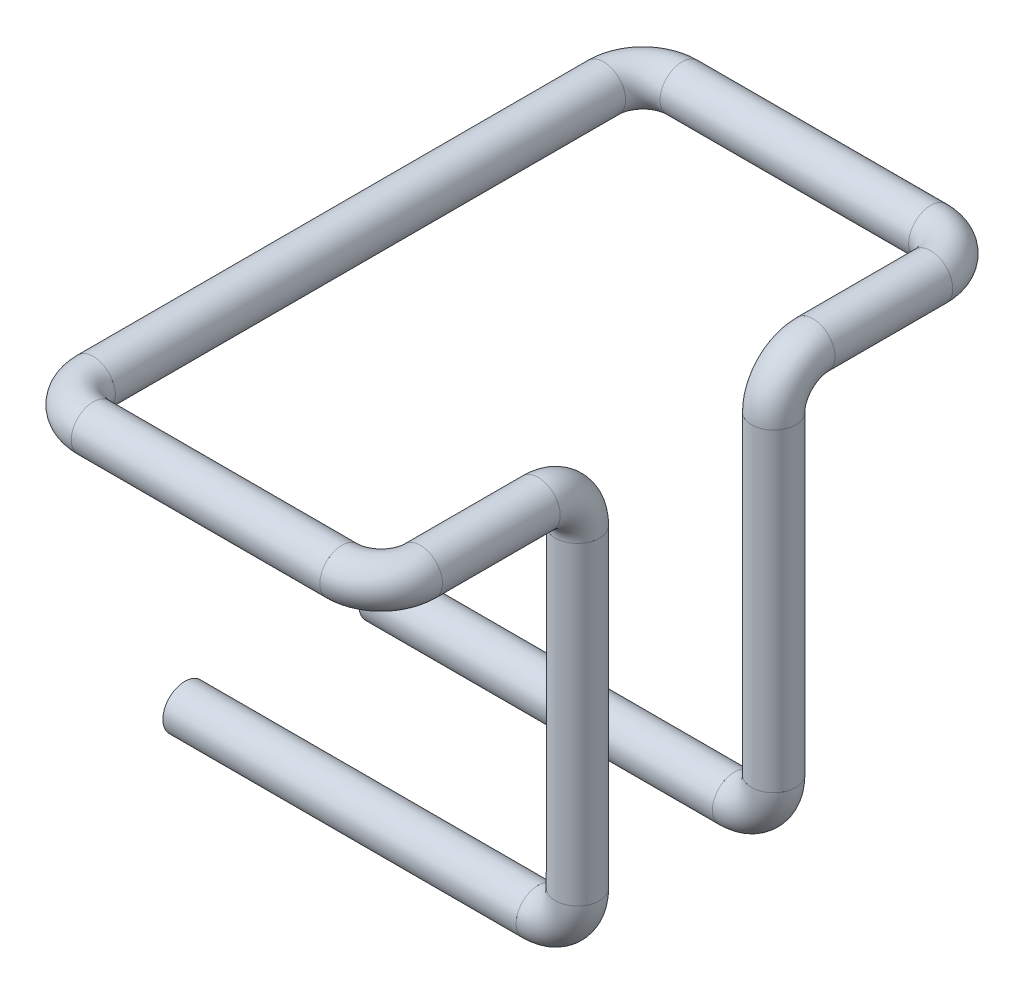
SolidWorks part; units mm, degrees
ref_plane "Front Plane" through (0, 0, 0) normal (0, 0, 1) x (1, 0, 0)
ref_plane "Top Plane" through (0, 0, 0) normal (0, 1, 0) x (1, 0, 0)
ref_plane "Right Plane" through (0, 0, 0) normal (1, 0, 0) x (0, 0, -1)
sketch3d "3DSketch1"
  line L0 (0, 0, 0) -> (270, 0, 0)
  line L1 (300, 30, 0) -> (300, 270, 0)
  line L2 (300, 300, -30) -> (300, 300, -120)
  line L3 (270, 300, -150) -> (80, 300, -150)
  line L4 (50, 300, -120) -> (50, 300, 270)
  line L5 (80, 300, 300) -> (270, 300, 300)
  line L6 (300, 300, 270) -> (300, 300, 180)
  line L7 (300, 270, 150) -> (300, 30, 150)
  line L8 (270, 0, 150) -> (0, 0, 150)
  arc A0 (300, 30, 0) -> (270, 0, 0) centre (270, 30, 0) ccw
  arc A1 (300, 30, 150) -> (270, 0, 150) centre (270, 30, 150) ccw
  arc A2 (300, 300, 270) -> (270, 300, 300) centre (270, 300, 270) ccw
  arc A3 (270, 300, -150) -> (300, 300, -120) centre (270, 300, -120) ccw
  arc A4 (80, 300, -150) -> (50, 300, -120) centre (80, 300, -120) ccw
  arc A5 (80, 300, 300) -> (50, 300, 270) centre (80, 300, 270) ccw
  arc A6 (300, 270, 0) -> (300, 300, -30) centre (300, 270, -30) ccw
  arc A7 (300, 270, 150) -> (300, 300, 180) centre (300, 270, 180) ccw
  point P13 (300, 0, 0)
  point P14 (270, 30, -30)
  point P17 (300, 0, 150)
  point P18 (270, 30, 120)
  point P21 (300, 300, 300)
  point P22 (270, 270, 270)
  point P25 (300, 300, -150)
  point P26 (270, 270, -120)
  point P29 (50, 300, -150)
  point P30 (80, 330, -120)
  point P33 (50, 300, 300)
  point P34 (80, 270, 270)
  point P37 (300, 300, 0)
  point P38 (270, 270, -30)
  point P41 (300, 300, 150)
  point P42 (330, 270, 180)
  dimension "D6" = 30
  dimension "D7" = 30
  dimension "D1" = 450
  dimension "D2" = 250
  dimension "D3" = 150
  dimension "D4" = 300
  dimension "D5" = 300
other "Pipe 33.7 X 4.0(1)"
ref_plane "Plane2" through (270, 0, 150) normal (-1, 0, 0) x (0, 0, 1)
sketch "Sketch1" plane through (270, 0, 150) normal (-1, 0, 0) x (0, 0, 1)
  circle A0 centre (0, 0) radius 12.85
  circle A1 centre (0, 0) radius 16.85
  point P3 (0, 16.85)
  point P5 (-16.85, 0)
  point P6 (0, -16.85)
  point P7 (16.85, 0)
  point P8 (0, 0)
  dimension "In_dia" = 25.7
  dimension "Out_dia" = 33.7
